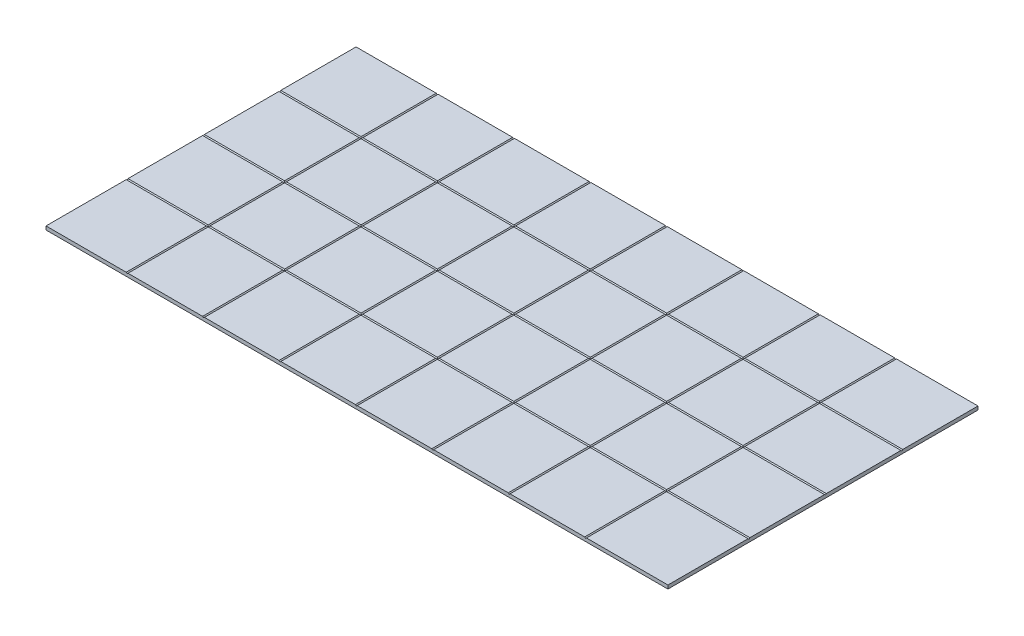
SolidWorks part; units mm, degrees
ref_plane "Front Plane" through (0, 0, 0) normal (0, 0, 1) x (1, 0, 0)
ref_plane "Top Plane" through (0, 0, 0) normal (0, 1, 0) x (1, 0, 0)
ref_plane "Right Plane" through (0, 0, 0) normal (1, 0, 0) x (0, 0, -1)
sketch "Sketch1" plane through (0, 0, 0) normal (0, 1, 0) x (1, 0, 0)
  line L1 (-174.5, 87) -> (174.5, 87)
  line L2 (-174.5, 87) -> (-174.5, -87)
  line L3 (-174.5, -87) -> (174.5, -87)
  line L4 (174.5, 87) -> (174.5, -87)
  line L5 (-174.5, 87) -> (174.5, -87) construction
  line L6 (-174.5, -87) -> (174.5, 87) construction
  point P0 (0, 0)
  dimension "D1" = 349
  dimension "D2" = 174
extrude "Boss-Extrude1" add sketch "Sketch1" along normal blind 2
sketch "Sketch2" plane through (0, 2, 0) normal (0, 1, 0) x (1, 0, 0)
  line L0 (174.5, -87) -> (174.5, -84)
  line L1 (-174.5, -87) -> (-171.5, -87)
  line L2 (-174.5, -87) -> (-174.5, -84)
  line L3 (-174.5, -84) -> (-171.5, -84)
  line L4 (-171.5, -87) -> (-171.5, -84)
  line L5 (-171.5, -84) -> (-129, -84)
  line L6 (-171.5, -84) -> (-171.5, -41.5)
  line L7 (-171.5, -41.5) -> (-129, -41.5)
  line L8 (-129, -84) -> (-129, -41.5)
  line L9 (171.5, -87) -> (174.5, -87)
  line L10 (171.5, -87) -> (171.5, -84)
  line L11 (171.5, -84) -> (174.5, -84)
  line L13 (-86.125, -84) -> (-86.125, -41.5)
  line L14 (-128.625, -41.5) -> (-86.125, -41.5)
  line L15 (-43.25, -84) -> (-43.25, -41.5)
  line L16 (-85.75, -41.5) -> (-43.25, -41.5)
  line L17 (-0.375, -84) -> (-0.375, -41.5)
  line L18 (-42.875, -41.5) -> (-0.375, -41.5)
  line L19 (42.5, -84) -> (42.5, -41.5)
  line L20 (0, -41.5) -> (42.5, -41.5)
  line L21 (85.375, -84) -> (85.375, -41.5)
  line L22 (42.875, -41.5) -> (85.375, -41.5)
  line L23 (128.25, -84) -> (128.25, -41.5)
  line L24 (85.75, -41.5) -> (128.25, -41.5)
  line L25 (171.125, -84) -> (171.125, -41.5)
  line L26 (128.625, -41.5) -> (171.125, -41.5)
  line L27 (-86.125, -41.125) -> (-86.125, 1.375)
  line L28 (-128.625, 1.375) -> (-86.125, 1.375)
  line L29 (-43.25, -41.125) -> (-43.25, 1.375)
  line L30 (-85.75, 1.375) -> (-43.25, 1.375)
  line L31 (-0.375, -41.125) -> (-0.375, 1.375)
  line L32 (-42.875, 1.375) -> (-0.375, 1.375)
  line L33 (42.5, -41.125) -> (42.5, 1.375)
  line L34 (0, 1.375) -> (42.5, 1.375)
  line L35 (85.375, -41.125) -> (85.375, 1.375)
  line L36 (42.875, 1.375) -> (85.375, 1.375)
  line L37 (128.25, -41.125) -> (128.25, 1.375)
  line L38 (85.75, 1.375) -> (128.25, 1.375)
  line L39 (171.125, -41.125) -> (171.125, 1.375)
  line L40 (128.625, 1.375) -> (171.125, 1.375)
  line L41 (-86.125, 1.75) -> (-86.125, 44.25)
  line L42 (-128.625, 44.25) -> (-86.125, 44.25)
  line L43 (-43.25, 1.75) -> (-43.25, 44.25)
  line L44 (-85.75, 44.25) -> (-43.25, 44.25)
  line L45 (-0.375, 1.75) -> (-0.375, 44.25)
  line L46 (-42.875, 44.25) -> (-0.375, 44.25)
  line L47 (42.5, 1.75) -> (42.5, 44.25)
  line L48 (0, 44.25) -> (42.5, 44.25)
  line L49 (85.375, 1.75) -> (85.375, 44.25)
  line L50 (42.875, 44.25) -> (85.375, 44.25)
  line L51 (128.25, 1.75) -> (128.25, 44.25)
  line L52 (85.75, 44.25) -> (128.25, 44.25)
  line L53 (171.125, 1.75) -> (171.125, 44.25)
  line L54 (128.625, 44.25) -> (171.125, 44.25)
  line L55 (-86.125, 44.625) -> (-86.125, 87.125)
  line L56 (-128.625, 87.125) -> (-86.125, 87.125)
  line L57 (-43.25, 44.625) -> (-43.25, 87.125)
  line L58 (-85.75, 87.125) -> (-43.25, 87.125)
  line L59 (-0.375, 44.625) -> (-0.375, 87.125)
  line L60 (-42.875, 87.125) -> (-0.375, 87.125)
  line L61 (42.5, 44.625) -> (42.5, 87.125)
  line L62 (0, 87.125) -> (42.5, 87.125)
  line L63 (85.375, 44.625) -> (85.375, 87.125)
  line L64 (42.875, 87.125) -> (85.375, 87.125)
  line L65 (128.25, 44.625) -> (128.25, 87.125)
  line L66 (85.75, 87.125) -> (128.25, 87.125)
  line L67 (171.125, 44.625) -> (171.125, 87.125)
  line L68 (128.625, 87.125) -> (171.125, 87.125)
  line L69 (-129, -41.125) -> (-129, 1.375)
  line L70 (-171.5, 1.375) -> (-129, 1.375)
  line L71 (-129, 1.75) -> (-129, 44.25)
  line L72 (-171.5, 44.25) -> (-129, 44.25)
  line L73 (-129, 44.625) -> (-129, 87.125)
  line L74 (-171.5, 87.125) -> (-129, 87.125)
  dimension "D1" = 3
  dimension "D2" = 3
  dimension "D3" = 3
  dimension "D4" = 3
  dimension "D5" = 42.5
  dimension "D6" = 42.5
  dimension "D7" = 343
  dimension "D8" = 8
  dimension "D9" = 4
ref_plane "Plane1" through (0, 0, 84) normal (0, 0, 1) x (1, 0, 0)
sketch "Sketch3" plane through (0, 0, 84) normal (0, 0, 1) x (1, 0, 0)
  line L0 (-129.5, 2) -> (-128.5, 2)
  line L1 (-128.5, 2) -> (-129, 1.5)
  line L2 (-129, 1.5) -> (-129.5, 2)
  point P3 (-129, 2)
  dimension "D1" = 1
  dimension "D2" = 0.5
  dimension "D3" = 0.5
extrude "Cut-Extrude1" cut sketch "Sketch3" against normal through all both and the other way through all
pattern_linear "LPattern1" count 7 spacing 42.88 along (1, 0, 0) of "Cut-Extrude1"
ref_plane "Plane2" through (171.125, 0, 0) normal (1, 0, 0) x (0, 0, -1)
sketch "Sketch4" plane through (171.125, 0, 0) normal (1, 0, 0) x (0, 0, -1)
  line L0 (-41.5, 2) -> (-41, 2)
  line L1 (-41, 2) -> (-41.5, 1.5)
  line L2 (-41.5, 1.5) -> (-42, 2)
  line L3 (-84, 2) -> (-41.5, 2) construction
  line L4 (-42, 2) -> (-41.5, 2)
  point P0 (-41.5, 2)
  dimension "D1" = 0.5
  dimension "D2" = 0.5
extrude "Cut-Extrude2" cut sketch "Sketch4" against normal through all both and the other way through all
pattern_linear "LPattern2" count 3 spacing 42.88 along (0, 0, -1) of "Cut-Extrude2"
